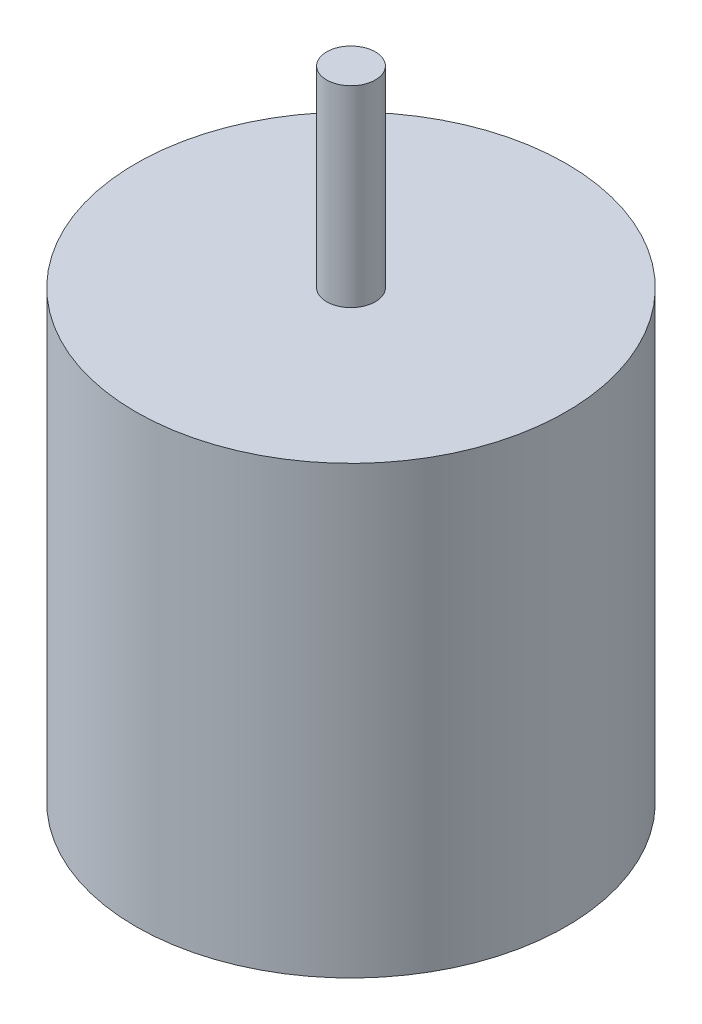
SolidWorks part; units mm, degrees
ref_plane "Plan de face" through (0, 0, 0) normal (0, 0, 1) x (1, 0, 0)
ref_plane "Plan de dessus" through (0, 0, 0) normal (0, 1, 0) x (1, 0, 0)
ref_plane "Plan de droite" through (0, 0, 0) normal (1, 0, 0) x (0, 0, -1)
other "Centre de masse"
sketch "Esquisse1" plane through (0, 0, 0) normal (0, 1, 0) x (1, 0, 0)
  circle A0 centre (0, 0) radius 14
extrude "Boss.-Extru.1" add sketch "Esquisse1" along normal blind 29
ref_point "Point1"
sketch "Esquisse2" plane through (0, 29, 0) normal (0, 1, 0) x (1, 0, 0)
  circle A0 centre (0, 0) radius 1.585
extrude "Boss.-Extru.2" add sketch "Esquisse2" along normal blind 12.5
